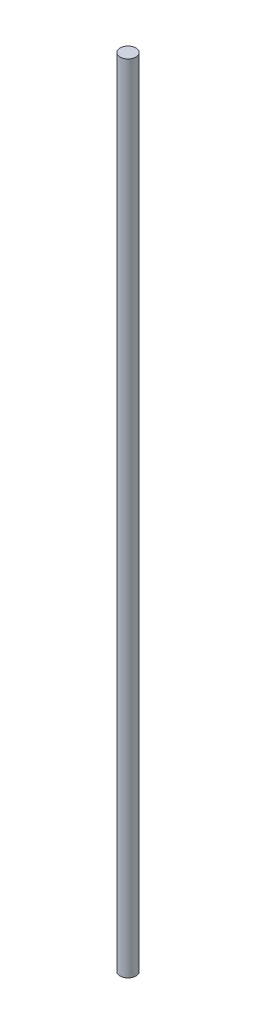
SolidWorks part; units mm, degrees
ref_plane "Front Plane" through (0, 0, 0) normal (0, 0, 1) x (1, 0, 0)
ref_plane "Top Plane" through (0, 0, 0) normal (0, 1, 0) x (1, 0, 0)
ref_plane "Right Plane" through (0, 0, 0) normal (1, 0, 0) x (0, 0, -1)
sketch "Sketch1" plane through (0, 0, 0) normal (0, 1, 0) x (1, 0, 0)
  circle A0 centre (0, 0) radius 1
  dimension "D1" = 2
extrude "Boss-Extrude1" add sketch "Sketch1" along normal blind 100
